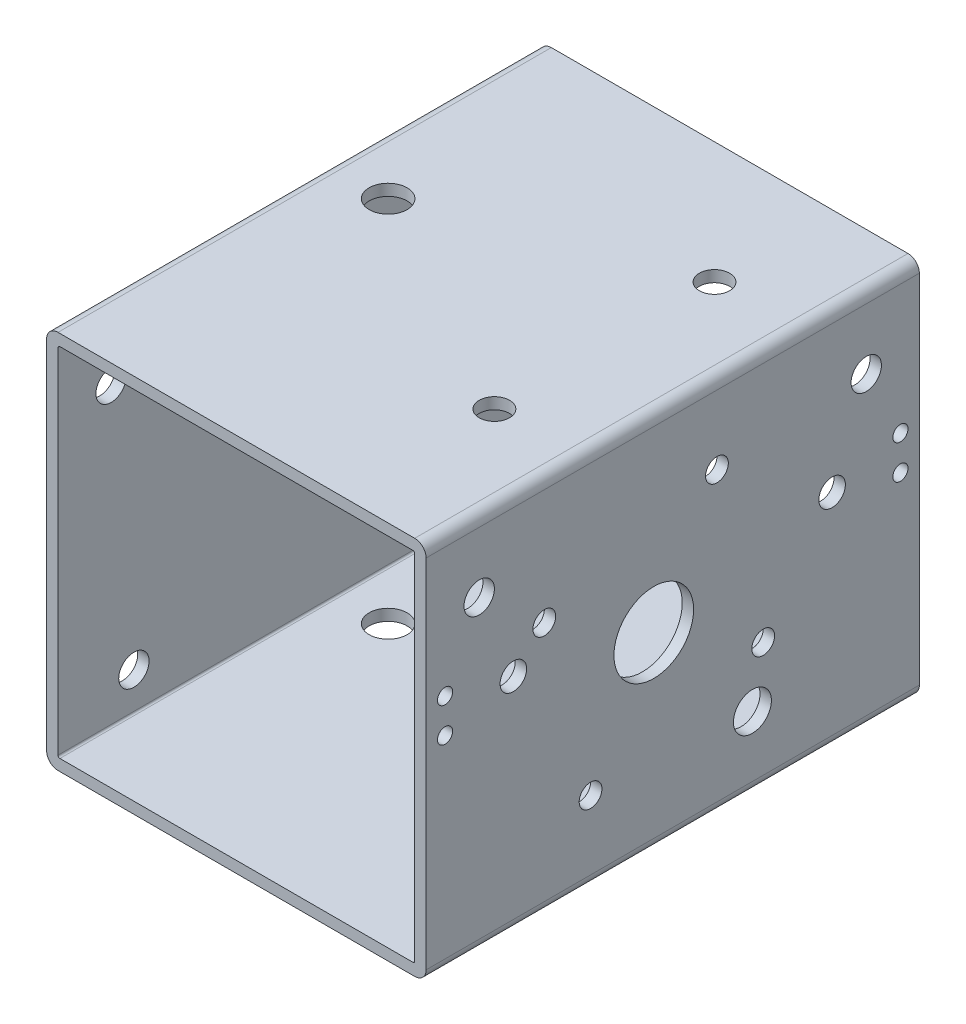
SolidWorks part; units mm, degrees
ref_plane "Front Plane" through (0, 0, 0) normal (0, 0, 1) x (1, 0, 0)
ref_plane "Top Plane" through (0, 0, 0) normal (0, 1, 0) x (1, 0, 0)
ref_plane "Right Plane" through (0, 0, 0) normal (1, 0, 0) x (0, 0, -1)
sketch "Sketch1" plane through (0, 0, 0) normal (0, 0, 1) x (1, 0, 0)
  line L1 (-50, 50) -> (50, 50)
  line L2 (-50, 50) -> (-50, -50)
  line L3 (-50, -50) -> (50, -50)
  line L4 (50, 50) -> (50, -50)
  line L5 (-50, 50) -> (50, -50) construction
  line L6 (-50, -50) -> (50, 50) construction
  point P0 (0, 0)
  dimension "D1" = 100
  dimension "D2" = 100
extrude "Extrude-Thin1" add sketch "Sketch1" along normal blind 130 thin
fillet "Fillet1" radius 0.5 4 edges at (-47, -47, 65) (-47, 47, 65) (47, 47, 65) (47, -47, 65)
fillet "Fillet2" radius 3 4 edges at (50, -50, 65) (-50, -50, 65) (50, 50, 65) (-50, 50, 65)
sketch "Holes - top" plane through (0, 0, 0) normal (0, 1, 0) x (1, 0, 0)
  line L0 (-3, 0) -> (-3, -130) construction
  line L1 (47, -130) -> (-47, -130) construction
  line L2 (-23, 0) -> (-23, -130) construction
  line L3 (47, 0) -> (-47, 0) construction
  line L4 (17, 0) -> (17, -130) construction
  circle A0 centre (-34, -56) radius 11 construction
  circle A1 centre (28, -90) radius 11 construction
  circle A2 centre (28, -32) radius 11 construction
  dimension "D4" = 22
  dimension "D1" = 40
  dimension "D2" = 40
  dimension "D3" = 32
  dimension "D5" = 56
  dimension "D6" = 3
hole_wizard "Ø8.0 (8) Diameter Hole2" positions "Sketch6" profile "Sketch5" hole size "Ø8.0" standard "ANSI Metric" end condition through all
sketch "Sketch6" plane through (0, 50, 0) normal (0, 1, 0) x (1, 0, 0)
  point P0 (28, -32)
  point P6 (28, -90)
sketch "Sketch5" plane through (28, 50, 32) normal (1, 0, 0) x (0, 0, 1)
  line L0 (0, 0) -> (0, 100)
  line L1 (0, 100) -> (4, 100)
  line L2 (4, 100) -> (4, 0)
  line L5 (4, 0) -> (0, 0)
  line L11 (0, -6.35) -> (0, 107.95) construction
  dimension "Thru Hole Dia." = 8
  dimension "Thru Hole Depth" = 100
sketch "Holes - side" plane through (0, 0, 0) normal (1, 0, 0) x (0, 0, -1)
  line L0 (0, 0) -> (-130, 0) construction
  line L1 (-130, -47) -> (-130, 47) construction
  line L2 (-130, 20) -> (0, 20) construction
  line L3 (0, -47) -> (0, 47) construction
  line L4 (-130, -20) -> (0, -20) construction
  circle A0 centre (-116, 31) radius 11 construction
  circle A1 centre (-14, 31) radius 11 construction
  circle A2 centre (-44, -31) radius 11 construction
  dimension "D1" = 40
  dimension "D2" = 22
  dimension "D3" = 14
  dimension "D4" = 14
  dimension "D5" = 44
hole_wizard "Ø8.0 (8) Diameter Hole3" positions "Sketch9" profile "Sketch8" hole size "Ø8.0" standard "ANSI Metric" end condition through all
sketch "Sketch9" plane through (50, 0, 0) normal (1, 0, 0) x (0, 0, -1)
  point P0 (-14, 31)
  point P3 (-116, 31)
sketch "Sketch8" plane through (50, 31, 14) normal (0, 1, 0) x (0, 0, -1)
  line L0 (0, 0) -> (0, 100)
  line L1 (0, 100) -> (4, 100)
  line L2 (4, 100) -> (4, 0)
  line L5 (4, 0) -> (0, 0)
  line L11 (0, -6.35) -> (0, 107.95) construction
  dimension "Thru Hole Dia." = 8
  dimension "Thru Hole Depth" = 100
hole_wizard "Ø10.0 (10) Diameter Hole1" positions "Sketch12" profile "Sketch11" hole size "Ø10.0" standard "ANSI Metric" end condition through all
sketch "Sketch12" plane through (0, 50, 0) normal (0, 1, 0) x (1, 0, 0)
  point P0 (-34, -56)
sketch "Sketch11" plane through (-34, 50, 56) normal (1, 0, 0) x (0, 0, 1)
  line L0 (0, 0) -> (0, 100)
  line L1 (0, 100) -> (5, 100)
  line L2 (5, 100) -> (5, 0)
  line L5 (5, 0) -> (0, 0)
  line L11 (0, -6.35) -> (0, 107.95) construction
  dimension "Thru Hole Dia." = 10
  dimension "Thru Hole Depth" = 100
hole_wizard "Ø10.0 (10) Diameter Hole2" positions "Sketch14" profile "Sketch13" hole size "Ø10.0" standard "ANSI Metric" end condition through all
sketch "Sketch14" plane through (50, 0, 0) normal (1, 0, 0) x (0, 0, -1)
  point P0 (-44, -31)
sketch "Sketch13" plane through (50, -31, 44) normal (0, 1, 0) x (0, 0, -1)
  line L0 (0, 0) -> (0, 100)
  line L1 (0, 100) -> (5, 100)
  line L2 (5, 100) -> (5, 0)
  line L5 (5, 0) -> (0, 0)
  line L11 (0, -6.35) -> (0, 107.95) construction
  dimension "Thru Hole Dia." = 10
  dimension "Thru Hole Depth" = 100
hole_wizard "Ø6.0 (6) Diameter Hole2" positions "Sketch18" profile "Sketch17" hole size "Ø6.0" standard "ANSI Metric"
sketch "Sketch18" plane through (-50, 0, 0) normal (-1, 0, 0) x (0, 0, 1)
  line L0 (56, 35) -> (56, -15) construction
  point P0 (56, -15)
  point P2 (56, 35)
  dimension "D1" = 56
  dimension "D2" = 35
  dimension "D3" = 15
sketch "Sketch17" plane through (-50, -15, 56) normal (0, 1, 0) x (0, 0, 1)
  line L0 (0, 0) -> (0, 3)
  line L1 (0, 3) -> (3, 3)
  line L2 (3, 3) -> (3, 0)
  line L5 (3, 0) -> (0, 0)
  line L11 (0, -6.35) -> (0, 107.95) construction
  dimension "Thru Hole Dia." = 6
  dimension "Thru Hole Depth" = 3
hole_wizard "Ø6.0 (6) Diameter Hole3" positions "Sketch21" profile "Sketch20" hole size "Ø6.0" standard "ANSI Metric"
sketch "Sketch21" plane through (0, -50, 0) normal (0, -1, 0) x (-1, 0, 0)
  line L0 (20, -44) -> (-35, -44) construction
  point P0 (20, -44)
  point P2 (-35, -44)
  dimension "D1" = 44
  dimension "D2" = 35
  dimension "D3" = 20
sketch "Sketch20" plane through (-20, -50, 44) normal (1, 0, 0) x (0, 0, -1)
  line L0 (0, 0) -> (0, 3)
  line L1 (0, 3) -> (3, 3)
  line L2 (3, 3) -> (3, 0)
  line L5 (3, 0) -> (0, 0)
  line L11 (0, -6.35) -> (0, 107.95) construction
  dimension "Thru Hole Dia." = 6
  dimension "Thru Hole Depth" = 3
sketch "Holes - Nema 23 motor" plane through (0, 0, 0) normal (1, 0, 0) x (0, 0, -1)
  line L0 (-98.8427, 16.6524) -> (-53.3476, 28.8427) construction
  line L1 (-98.8427, 16.6524) -> (-86.6524, -28.8427) construction
  line L2 (-53.3476, 28.8427) -> (-41.1573, -16.6524) construction
  line L3 (-86.6524, -28.8427) -> (-41.1573, -16.6524) construction
  line L4 (-98.8427, 16.6524) -> (-41.1573, -16.6524) construction
  line L5 (-53.3476, 28.8427) -> (-86.6524, -28.8427) construction
  line L6 (0, 0) -> (-130, 0) construction
  point P1 (-70, 0)
  dimension "D1" = 70
  dimension "D2" = 47.1
  dimension "D3" = 47.1
  dimension "D4" = 15
hole_wizard "Ø21.0 (21) Diameter Hole1" positions "Sketch24" profile "Sketch23" hole size "Ø21.0" standard "ANSI Metric"
sketch "Sketch24" plane through (50, 0, 0) normal (1, 0, 0) x (0, 0, -1)
  point P0 (-70, 0)
sketch "Sketch23" plane through (50, 0, 70) normal (0, 1, 0) x (0, 0, -1)
  line L0 (0, 0) -> (0, 3)
  line L1 (0, 3) -> (10.5, 3)
  line L2 (10.5, 3) -> (10.5, 0)
  line L5 (10.5, 0) -> (0, 0)
  line L11 (0, -6.35) -> (0, 107.95) construction
  dimension "Thru Hole Dia." = 21
  dimension "Thru Hole Depth" = 3
hole_wizard "Ø6.0 (6) Diameter Hole1" positions "Sketch26" profile "Sketch25" hole size "Ø6.0" standard "ANSI Metric"
sketch "Sketch26" plane through (50, 0, 0) normal (1, 0, 0) x (0, 0, -1)
  point P0 (-41.1573, -16.6524)
  point P3 (-53.3476, 28.8427)
  point P6 (-98.8427, 16.6524)
  point P9 (-86.6524, -28.8427)
sketch "Sketch25" plane through (50, -16.6524, 41.1573) normal (0, 1, 0) x (0, 0, -1)
  line L0 (0, 0) -> (0, 3)
  line L1 (0, 3) -> (3, 3)
  line L2 (3, 3) -> (3, 0)
  line L5 (3, 0) -> (0, 0)
  line L11 (0, -6.35) -> (0, 107.95) construction
  dimension "Thru Hole Dia." = 6
  dimension "Thru Hole Depth" = 3
sketch "Sketch27" plane through (50, 0, 0) normal (1, 0, 0) x (0, 0, -1)
  line L1 (0, -47) -> (0, 47) construction
  line L2 (-130, 50) -> (0, 50) construction
  line L3 (-65, 66.9997) -> (-65, -40.3101) construction
  line L4 (-130, -47) -> (-130, 47) construction
  circle A0 centre (-5, 13) radius 2
  circle A1 centre (-5, 4) radius 2
  circle A2 centre (-23, 8.5) radius 3.5
  circle A3 centre (-107, 8.5) radius 3.5
  circle A4 centre (-125, 4) radius 2
  circle A5 centre (-125, 13) radius 2
  dimension "D1" = 4
  dimension "D2" = 9
  dimension "D3" = 5
  dimension "D4" = 46
  dimension "D7" = 18
  dimension "D8" = 4.5
  dimension "D9" = 7
  dimension "D5" = 0
  dimension "D6" = 65
extrude "Cut-Extrude1" cut sketch "Sketch27" against normal up to next
sketch "Sketch31" plane through (-50, 0, 0) normal (-1, 0, 0) x (0, 0, 1)
  line L0 (0, 47) -> (0, -47) construction
  line L1 (130, 47) -> (130, -47) construction
  line L2 (0, -47) -> (130, -47) construction
  circle A0 centre (14, -37) radius 4
  circle A1 centre (110, -37) radius 4
  dimension "D1" = 8
  dimension "D2" = 8
  dimension "D3" = 14
  dimension "D4" = 20
  dimension "D5" = 10
extrude "Cut-Extrude2" cut sketch "Sketch31" against normal up to next
equation "\"L\"= 130"
equation "\"D1@Extrude-Thin1\"=\"L\""
equation "\"d-bearing\"= 22'diameter of bearing"
equation "\"D4@Holes - top\"=\"d-bearing\""
equation "\"D2@Holes - side\"=\"d-bearing\""
